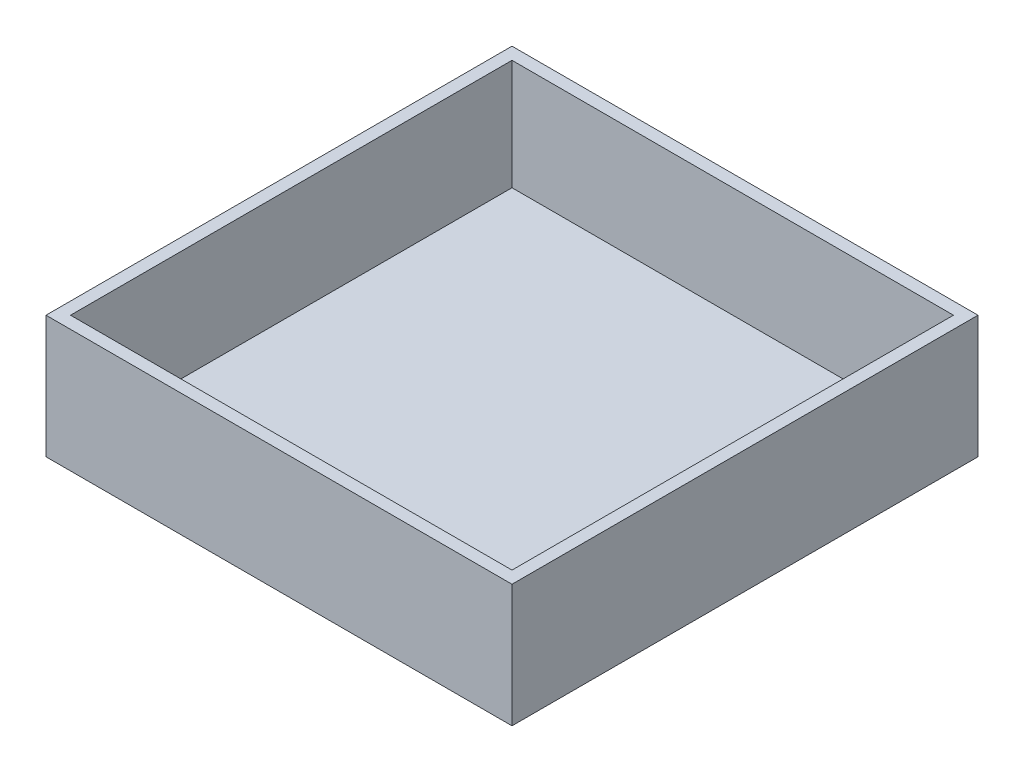
SolidWorks part; units mm, degrees
ref_plane "Front Plane" through (0, 0, 0) normal (0, 0, 1) x (1, 0, 0)
ref_plane "Top Plane" through (0, 0, 0) normal (0, 1, 0) x (1, 0, 0)
ref_plane "Right Plane" through (0, 0, 0) normal (1, 0, 0) x (0, 0, -1)
sketch "Sketch1" plane through (0, 0, 0) normal (0, 1, 0) x (1, 0, 0)
  line L0 (-95, -95) -> (-95, 95)
  line L1 (-90, -90) -> (90, -90)
  line L2 (-90, -90) -> (-90, 90)
  line L3 (-90, 90) -> (90, 90)
  line L4 (90, -90) -> (90, 90)
  line L5 (-90, -90) -> (90, 90) construction
  line L6 (-90, 90) -> (90, -90) construction
  line L7 (-95, 95) -> (95, 95)
  line L8 (95, -95) -> (95, 95)
  line L9 (-95, -95) -> (95, -95)
  point P0 (0, 0)
  dimension "D1" = 180
  dimension "D2" = 180
extrude "Boss-Extrude1" add sketch "Sketch1" along normal blind 45
sketch "Sketch2" plane through (0, 0, 0) normal (0, -1, 0) x (1, 0, 0)
  line L1 (-95, 95) -> (95, 95)
  line L2 (-95, 95) -> (-95, -95)
  line L3 (-95, -95) -> (95, -95)
  line L4 (95, 95) -> (95, -95)
extrude "Boss-Extrude2" add sketch "Sketch2" along normal blind 5
